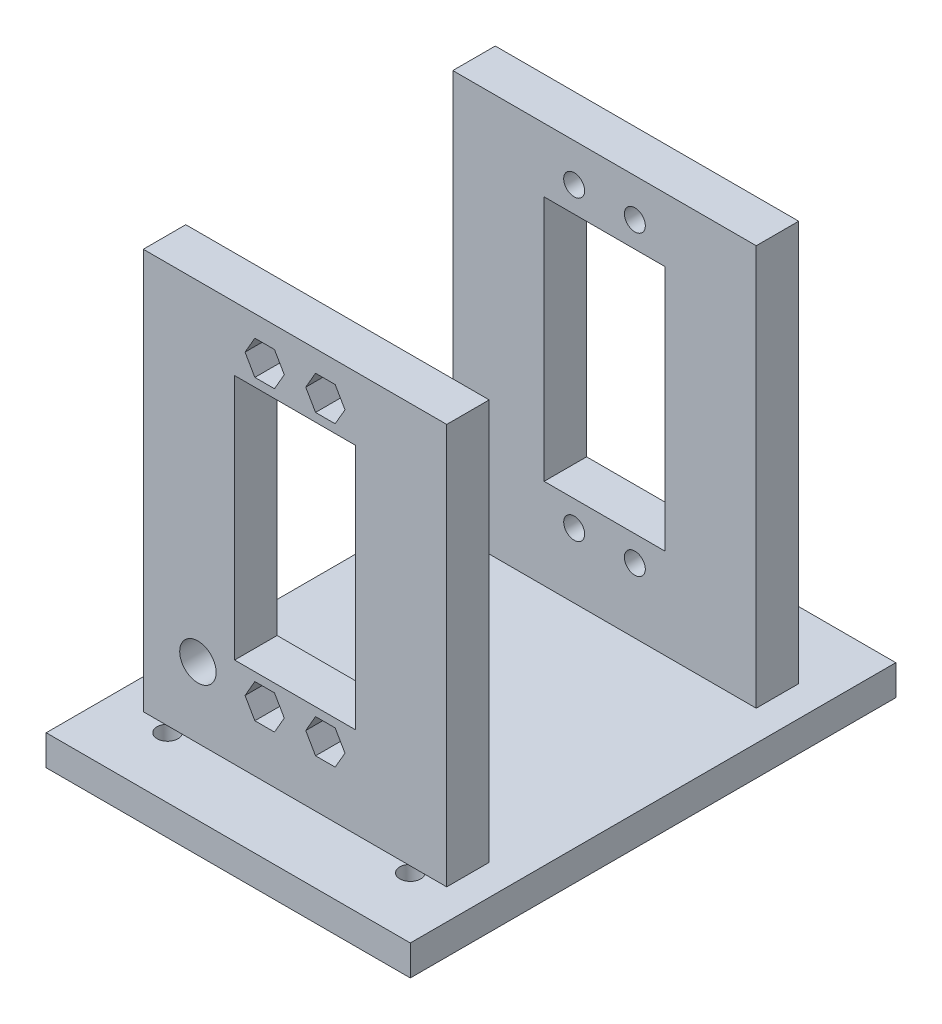
SolidWorks part; units mm, degrees
material "PLA Makeshift"
ref_plane "Front Plane" through (0, 0, 0) normal (0, 0, 1) x (1, 0, 0)
ref_plane "Top Plane" through (0, 0, 0) normal (0, 1, 0) x (1, 0, 0)
ref_plane "Right Plane" through (0, 0, 0) normal (1, 0, 0) x (0, 0, -1)
sketch "Sketch1" plane through (0, 0, 0) normal (0, 1, 0) x (1, 0, 0)
  line L1 (-30, -40) -> (30, -40)
  line L2 (-30, -40) -> (-30, 40)
  line L3 (-30, 40) -> (30, 40)
  line L4 (30, -40) -> (30, 40)
  line L5 (-30, -40) -> (30, 40) construction
  line L6 (-30, 40) -> (30, -40) construction
  point P0 (0, 0)
  dimension "D1" = 80
  dimension "D2" = 60
extrude "Boss-Extrude1" add sketch "Sketch1" along normal mid plane 5
sketch "Sketch2" plane through (0, 2.5, 0) normal (0, 1, 0) x (1, 0, 0)
  line L0 (30, -40) -> (30, 40) construction
  line L2 (-30, 40) -> (-30, -40) construction
  line L3 (-30, -40) -> (30, -40) construction
  circle A0 centre (-20, 30) radius 1.725
  circle A1 centre (20, 30) radius 1.725
  circle A2 centre (20, -30) radius 1.725
  circle A3 centre (-20, -30) radius 1.725
  dimension "D1" = 3.45
  dimension "D2" = 40
  dimension "D3" = 10
  dimension "D4" = 60
  dimension "D5" = 60
  dimension "D6" = 40
  dimension "D7" = 10
  dimension "D8" = 10
  dimension "D9" = 10
extrude "Cut-Extrude1" cut sketch "Sketch2" against normal through all
ref_plane "Plane1" through (0, 0, 22) normal (0, 0, 1) x (1, 0, 0)
sketch "Sketch3" plane through (0, 0, 22) normal (0, 0, 1) x (1, 0, 0)
  line L1 (-25, 2.5) -> (25, 2.5)
  line L2 (-25, 2.5) -> (-25, 68.5)
  line L3 (-25, 68.5) -> (25, 68.5)
  line L4 (25, 2.5) -> (25, 68.5)
  dimension "D1" = 50
  dimension "D2" = 25
  dimension "D3" = 66
  dimension "D4" = 2.5
extrude "Boss-Extrude2" add sketch "Sketch3" along normal blind 7
mirror "Mirror1" about plane through (0, 0, 0) normal (0, 0, 1) of "Boss-Extrude2"
sketch "Sketch4" plane through (0, 0, 29) normal (0, 0, 1) x (1, 0, 0)
  line L1 (-9.95, 58) -> (9.95, 58)
  line L2 (-9.95, 58) -> (-9.95, 17.4)
  line L3 (-9.95, 17.4) -> (9.95, 17.4)
  line L4 (9.95, 58) -> (9.95, 17.4)
  dimension "D1" = 19.9
  dimension "D2" = 9.95
  dimension "D3" = 40.6
  dimension "D4" = 17.4
extrude "Cut-Extrude2" cut sketch "Sketch4" against normal through all
sketch "Sketch5" plane through (0, 0, 29) normal (0, 0, 1) x (1, 0, 0)
  circle A0 centre (-5, 62.2) radius 1.725
  circle A1 centre (5, 62.2) radius 1.725
  circle A2 centre (-5, 13.2) radius 1.725
  circle A3 centre (5, 13.2) radius 1.725
  dimension "D9" = 3.45
  dimension "D1" = 5
  dimension "D2" = 5
  dimension "D3" = 13.2
  dimension "D4" = 13.2
  dimension "D5" = 62.2
  dimension "D6" = 62.2
  dimension "D7" = 5
  dimension "D8" = 5
extrude "Cut-Extrude3" cut sketch "Sketch5" against normal through all
sketch "Sketch6" plane through (0, 0, 29) normal (0, 0, 1) x (1, 0, 0)
  line L1 (-1.7668, 62.2) -> (-3.3834, 65)
  line L2 (-3.3834, 65) -> (-6.6166, 65)
  line L3 (-6.6166, 65) -> (-8.2332, 62.2)
  line L4 (-8.2332, 62.2) -> (-6.6166, 59.4)
  line L5 (-6.6166, 59.4) -> (-3.3834, 59.4)
  line L6 (-3.3834, 59.4) -> (-1.7668, 62.2)
  line L7 (1.7668, 62.2) -> (3.3834, 59.4)
  line L8 (3.3834, 59.4) -> (6.6166, 59.4)
  line L9 (6.6166, 59.4) -> (8.2332, 62.2)
  line L10 (8.2332, 62.2) -> (6.6166, 65)
  line L11 (6.6166, 65) -> (3.3834, 65)
  line L12 (3.3834, 65) -> (1.7668, 62.2)
  line L13 (-1.7668, 13.2) -> (-3.3834, 16)
  line L14 (-3.3834, 16) -> (-6.6166, 16)
  line L15 (-6.6166, 16) -> (-8.2332, 13.2)
  line L16 (-8.2332, 13.2) -> (-6.6166, 10.4)
  line L17 (-6.6166, 10.4) -> (-3.3834, 10.4)
  line L18 (-3.3834, 10.4) -> (-1.7668, 13.2)
  line L19 (8.2332, 13.2) -> (6.6166, 16)
  line L20 (6.6166, 16) -> (3.3834, 16)
  line L21 (3.3834, 16) -> (1.7668, 13.2)
  line L22 (1.7668, 13.2) -> (3.3834, 10.4)
  line L23 (3.3834, 10.4) -> (6.6166, 10.4)
  line L24 (6.6166, 10.4) -> (8.2332, 13.2)
  circle A0 centre (-5, 62.2) radius 2.8 construction
  circle A1 centre (5, 62.2) radius 2.8 construction
  circle A2 centre (-5, 13.2) radius 2.8 construction
  circle A3 centre (5, 13.2) radius 2.8 construction
extrude "Cut-Extrude4" cut sketch "Sketch6" against normal blind 4.2
mirror "Mirror3" about plane through (0, 0, 0) normal (0, 0, 1) of "Cut-Extrude4"
sketch "Sketch7" plane through (0, 0, 0) normal (0, 0, 1) x (1, 0, 0)
  circle A0 centre (-16, 14.1) radius 3
extrude "Cut-Extrude5" cut sketch "Sketch7" along normal blind 9 from offset 21
